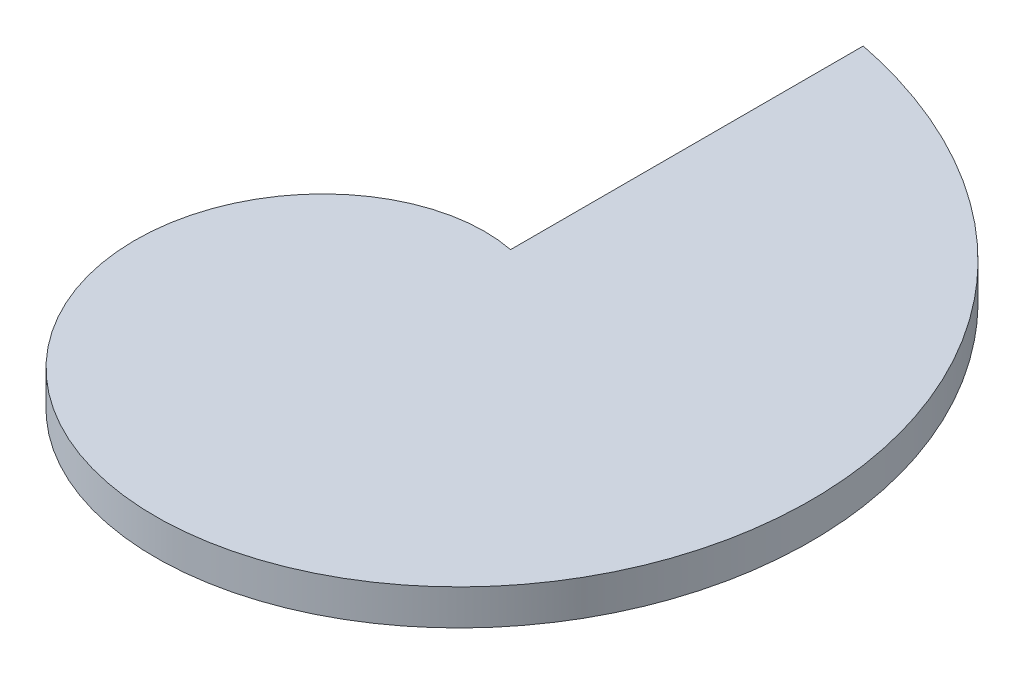
SolidWorks part; units mm, degrees
ref_plane "Front Plane" through (0, 0, 0) normal (0, 0, 1) x (1, 0, 0)
ref_plane "Top Plane" through (0, 0, 0) normal (0, 1, 0) x (1, 0, 0)
ref_plane "Right Plane" through (0, 0, 0) normal (1, 0, 0) x (0, 0, -1)
sketch "Sketch1" plane through (0, 0, 0) normal (0, 1, 0) x (1, 0, 0)
  line L0 (0, 0) -> (0, 41.5711) construction
  line L1 (-35, 45) -> (35, 45) construction
  line L2 (-35, 45) -> (-35, -45) construction
  line L3 (-35, -45) -> (35, -45) construction
  line L4 (35, 45) -> (35, -45) construction
  line L5 (-35, 45) -> (35, -45) construction
  line L6 (-35, -45) -> (35, 45) construction
  line L7 (0, 41.5711) -> (0, 11.8319)
  spline S0 degree 4 poles (8.7508, 0.6885) (8.7762, 0.9014) (8.8135, 1.3286) (8.8288, 1.9723) (8.7694, 2.8287) (8.6495, 3.5683) (8.5005, 4.1904) (8.347, 4.6979) (8.2078, 5.0954) (8.0518, 5.4865) (7.8793, 5.8708) (7.7145, 6.2001) (7.5755, 6.4552) (7.4719, 6.6353) (7.4043, 6.7488) (7.3476, 6.8417) (7.2734, 6.9602) (7.1827, 7.1013) (7.1161, 7.2011) (7.0198, 7.3406) (6.9374, 7.4567) (6.8725, 7.5461) (6.7924, 7.6537) (6.6637, 7.8216) (6.512, 8.0105) (6.3385, 8.2145) (6.1597, 8.4139) (6.0133, 8.5705) (5.8265, 8.7625) (5.5963, 8.9869) (5.3192, 9.2397) (4.9664, 9.5369) (4.5752, 9.8385) (4.0291, 10.2204) (3.3108, 10.6545) (2.4335, 11.0906) (1.3482, 11.5049) (0.1863, 11.8202) (-1.0434, 12.022) (-2.3293, 12.0966) (-3.6161, 12.0392) (-4.8904, 11.8529) (-6.1403, 11.5422) (-7.3542, 11.1125) (-8.5219, 10.5697) (-9.6341, 9.9209) (-10.9446, 8.9865) (-12.3747, 7.6836) (-13.8075, 5.9342) (-15.0855, 3.689) (-15.9814, 1.2667) (-16.4847, -1.2658) (-16.5955, -3.8448) (-16.3231, -6.4112) (-15.6844, -8.9112) (-14.457, -11.8932) (-12.3534, -15.1593) (-9.1183, -18.3582) (-3.9079, -21.4165) (3.2631, -23.1907) (10.6821, -22.4181) (17.4048, -19.376) (22.4222, -15.2947) (25.7571, -11.3408) (28.3277, -6.8552) (30.0819, -1.9935) (30.997, 3.0914) (31.0761, 8.2561) (30.4353, 12.7288) (29.4053, 16.4549) (28.244, 19.4555) (27.1411, 21.7811) (25.5554, 24.5805) (23.7085, 27.2192) (21.6238, 29.6739) (19.3263, 31.9257) (17.3708, 33.5987) (15.3081, 35.1376) (13.1487, 36.5375) (10.903, 37.7941) (8.5813, 38.9041) (6.4925, 39.7447) (4.6674, 40.3709) (3.2809, 40.7835) (2.3495, 41.0347) (1.6479, 41.2088) (1.1777, 41.319) (0.786, 41.4067) (0.4798, 41.4729) (0.0671, 41.5583) (-0.1665, 41.6045) (-0.5766, 41.6832) (-0.917, 41.7445) (-1.297, 41.8107) (-1.8497, 41.9009) (-2.5958, 42.011) (-3.4648, 42.1218) (-4.4628, 42.2257) (-5.4618, 42.3063) (-6.4631, 42.3639) (-7.465, 42.3985) (-8.4676, 42.4102) (-9.4702, 42.3991) (-10.4723, 42.3654) (-11.7236, 42.2949) (-13.2222, 42.1655) (-14.4663, 42.0114) (-15.4573, 41.8589) (-15.9516, 41.7754) knots 0 0 0 0 0 0.004678 0.009356 0.014035 0.018713 0.02101 0.023308 0.025605 0.027903 0.0302 0.032497 0.033646 0.034221 0.034795 0.035369 0.035944 0.037092 0.038262 0.038846 0.039431 0.040016 0.040601 0.04177 0.044109 0.045278 0.046448 0.047617 0.048787 0.051125 0.053464 0.055803 0.058853 0.061904 0.068004 0.074105 0.080205 0.087222 0.094238 0.101255 0.108272 0.115288 0.122305 0.129322 0.136338 0.143355 0.150372 0.164405 0.178438 0.192472 0.206505 0.220538 0.234572 0.248605 0.262638 0.276672 0.304739 0.332805 0.360872 0.407263 0.463396 0.491463 0.519529 0.547596 0.575663 0.603729 0.631796 0.659863 0.687929 0.701963 0.715996 0.730029 0.744063 0.772129 0.786163 0.800196 0.81423 0.828263 0.842296 0.85633 0.870363 0.884396 0.891413 0.89843 0.901938 0.905446 0.907201 0.908955 0.910709 0.912463 0.915199 0.916566 0.917934 0.92067 0.923405 0.928876 0.934347 0.939818 0.945289 0.95076 0.956232 0.961703 0.967174 0.972645 0.978116 0.989058 1 1 1 1 1 construction
  spline S1 degree 4 poles (0, 11.8319) (-0.1021, 11.8523) (-0.5203, 11.9309) (-1.2608, 12.0346) (-2.3293, 12.0966) (-3.6161, 12.0392) (-4.8904, 11.8529) (-6.1403, 11.5422) (-7.3542, 11.1125) (-8.5219, 10.5697) (-9.6341, 9.9209) (-10.9446, 8.9865) (-12.3747, 7.6836) (-13.8075, 5.9342) (-15.0855, 3.689) (-15.9814, 1.2667) (-16.4847, -1.2658) (-16.5955, -3.8448) (-16.3231, -6.4112) (-15.6844, -8.9112) (-14.457, -11.8932) (-12.3534, -15.1593) (-9.1183, -18.3582) (-3.9079, -21.4165) (3.2631, -23.1907) (10.6821, -22.4181) (17.4048, -19.376) (22.4222, -15.2947) (25.7571, -11.3408) (28.3277, -6.8552) (30.0819, -1.9935) (30.997, 3.0914) (31.0761, 8.2561) (30.4353, 12.7288) (29.4053, 16.4549) (28.244, 19.4555) (27.1411, 21.7811) (25.5554, 24.5805) (23.7085, 27.2192) (21.6238, 29.6739) (19.3263, 31.9257) (17.3708, 33.5987) (15.3081, 35.1376) (13.1487, 36.5375) (10.903, 37.7941) (8.5813, 38.9041) (6.4925, 39.7447) (4.6674, 40.3709) (3.2809, 40.7835) (2.3495, 41.0347) (1.6479, 41.2088) (1.1777, 41.319) (0.786, 41.4067) (0.48, 41.4729) (0.2086, 41.529) (0.0689, 41.5574) (0, 41.5711) knots 0.08495 0.08495 0.08495 0.08495 0.08495 0.087222 0.094238 0.101255 0.108272 0.115288 0.122305 0.129322 0.136338 0.143355 0.150372 0.164405 0.178438 0.192472 0.206505 0.220538 0.234572 0.248605 0.262638 0.276672 0.304739 0.332805 0.360872 0.407263 0.463396 0.491463 0.519529 0.547596 0.575663 0.603729 0.631796 0.659863 0.687929 0.701963 0.715996 0.730029 0.744063 0.772129 0.786163 0.800196 0.81423 0.828263 0.842296 0.85633 0.870363 0.884396 0.891413 0.89843 0.901938 0.905446 0.907201 0.908955 0.910709 0.91246 0.91246 0.91246 0.91246 0.91246
  point P1 (0, 0)
  point P9 (0, 0)
  dimension "D1" = 70
  dimension "D2" = 90
extrude "Boss-Extrude2" add sketch "Sketch1" along normal blind 3 contours S1 L7
